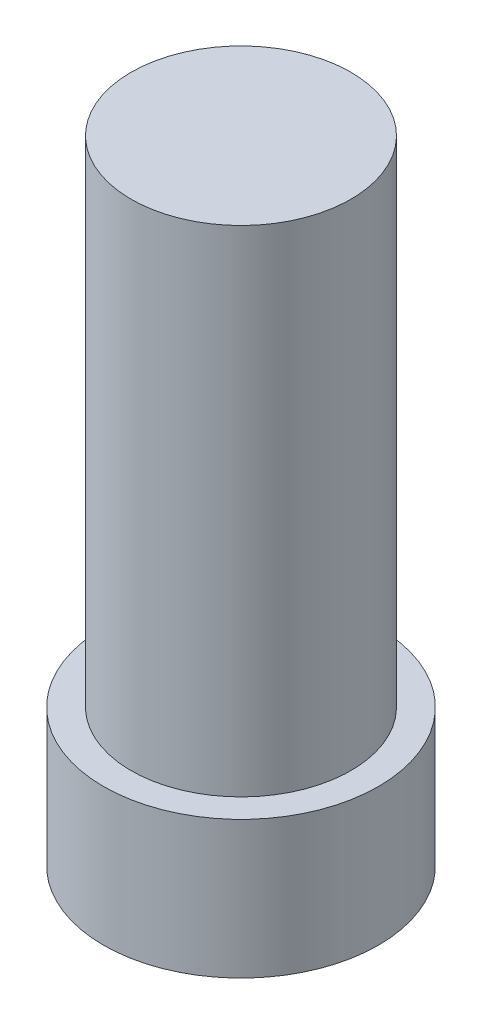
SolidWorks part; units mm, degrees
material "K110"
ref_plane "Front Plane" through (0, 0, 0) normal (0, 0, 1) x (1, 0, 0)
ref_plane "Top Plane" through (0, 0, 0) normal (0, 1, 0) x (1, 0, 0)
ref_plane "Right Plane" through (0, 0, 0) normal (1, 0, 0) x (0, 0, -1)
sketch "Sketch1" plane through (0, 0, 0) normal (0, 0, 1) x (1, 0, 0)
  line L0 (0, 0) -> (4, 0)
  line L1 (4, 0) -> (4, -18)
  line L2 (4, -18) -> (5, -18)
  line L3 (5, -18) -> (5, -23)
  line L4 (5, -23) -> (0, -23)
  line L5 (0, -23) -> (0, 0)
  line L6 (0, 5) -> (0, -28) construction
  point P9 (2, 0)
  dimension "D1" = 5
  dimension "D2" = 5
  dimension "D3" = 8
  dimension "D4" = 10
  dimension "D5" = 5
  dimension "D6" = 18
revolve "Revolve1" add sketch "Sketch1" angle 360 about L6
